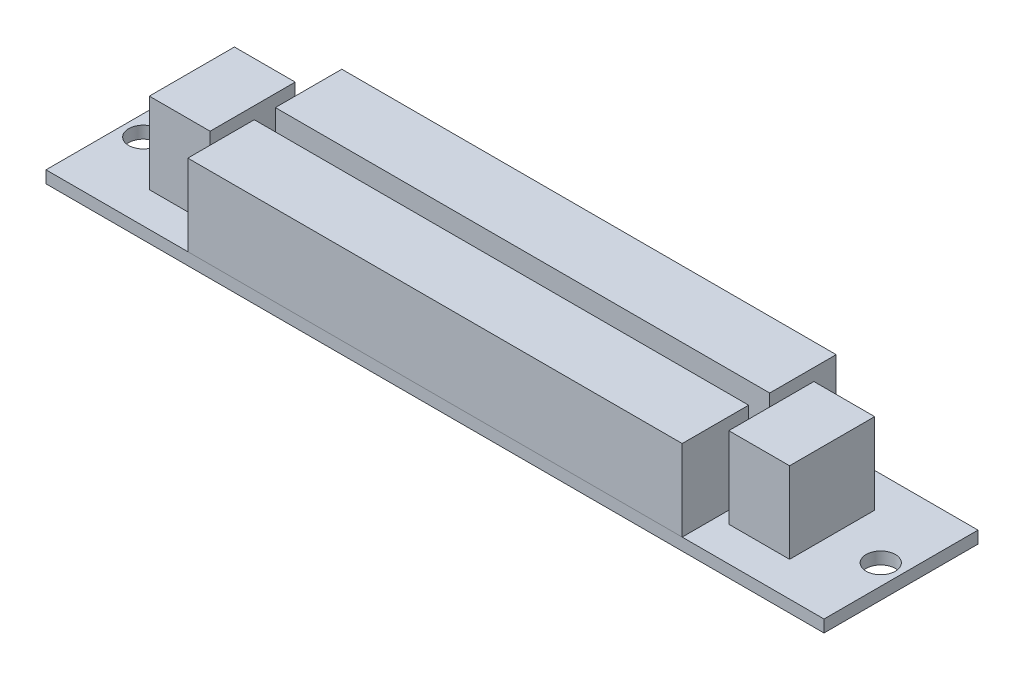
SolidWorks part; units mm, degrees
ref_plane "Front Plane" through (0, 0, 0) normal (0, 0, 1) x (1, 0, 0)
ref_plane "Top Plane" through (0, 0, 0) normal (0, 1, 0) x (1, 0, 0)
ref_plane "Right Plane" through (0, 0, 0) normal (1, 0, 0) x (0, 0, -1)
sketch "Sketch1" plane through (0, 0, 0) normal (0, 1, 0) x (1, 0, 0)
  line L1 (0, 0) -> (96, 0)
  line L2 (0, 0) -> (0, 19)
  line L3 (0, 19) -> (96, 19)
  line L4 (96, 0) -> (96, 19)
  dimension "D1" = 96
  dimension "D2" = 19
extrude "Boss-Extrude1" add sketch "Sketch1" along normal blind 1.5
sketch "Sketch2" plane through (0, 1.5, 0) normal (0, 1, 0) x (1, 0, 0)
  line L0 (0, 9.5) -> (96, 9.5) construction
  line L1 (0, 19) -> (0, 0) construction
  line L2 (96, 0) -> (96, 19) construction
  line L3 (0, 0) -> (96, 0) construction
  line L4 (8.5, 19) -> (87.5, 19)
  line L5 (8.5, 19) -> (8.5, 0)
  line L6 (8.5, 0) -> (87.5, 0)
  line L7 (87.5, 19) -> (87.5, 0)
  line L8 (8.5, 19) -> (87.5, 0) construction
  line L9 (8.5, 0) -> (87.5, 19) construction
  point P6 (48, 9.5)
  dimension "D1" = 79
extrude "Boss-Extrude2" add sketch "Sketch2" along normal blind 10 separate body
sketch "Sketch3" plane through (0, 1.5, 0) normal (0, 1, 0) x (1, 0, 0)
  line L0 (48, 19) -> (48, 0) construction
  line L1 (87.5, 19) -> (8.5, 19) construction
  line L2 (8.5, 0) -> (87.5, 0) construction
  line L3 (2.5, 9.5) -> (93.5, 9.5) construction
  point P7 (93.5, 9.5)
  point P8 (2.5, 9.5)
  point P9 (48, 9.5)
  dimension "D1" = 91
hole_wizard "M3 Clearance Hole1" positions "Sketch3" profile "Sketch4" hole size "M3" standard "ANSI Metric"
sketch "Sketch4" plane through (2.5, 1.5, -9.5) normal (1, 0, 0) x (0, 0, 1)
  line L0 (0, 0) -> (0, 1.5)
  line L1 (0, 1.5) -> (1.8, 1.5)
  line L2 (1.8, 1.5) -> (1.8, 0)
  line L5 (1.8, 0) -> (0, 0)
  line L11 (0, -6.35) -> (0, 107.95) construction
  dimension "Thru Hole Dia." = 3.6
  dimension "Thru Hole Depth" = 1.5
sketch "Sketch5" plane through (0, 11.5, 0) normal (0, 1, 0) x (1, 0, 0)
  line L0 (8.5, 9.5) -> (87.5, 9.5) construction
  line L1 (8.5, 19) -> (8.5, 0) construction
  line L2 (87.5, 0) -> (87.5, 19) construction
  line L3 (8.5, 9.5) -> (16, 9.5) construction
  line L4 (8.5, 4.25) -> (16, 4.25) construction
  line L5 (8.5, 4.25) -> (8.5, 14.75) construction
  line L6 (8.5, 14.75) -> (16, 14.75) construction
  line L7 (16, 4.25) -> (16, 14.75) construction
  line L8 (8.5, 0) -> (87.5, 0) construction
  line L9 (16, 14.75) -> (8.5, 14.75)
  line L10 (16, 14.75) -> (16, 19)
  line L11 (16, 19) -> (8.5, 19)
  line L12 (8.5, 14.75) -> (8.5, 19)
  line L13 (16, 4.25) -> (8.5, 4.25)
  line L14 (16, 4.25) -> (16, 0)
  line L15 (16, 0) -> (8.5, 0)
  line L16 (8.5, 4.25) -> (8.5, 0)
  line L17 (78.5, 8.2) -> (17.5, 8.2)
  line L18 (78.5, 8.2) -> (78.5, 10.8)
  line L19 (78.5, 10.8) -> (17.5, 10.8)
  line L20 (17.5, 8.2) -> (17.5, 10.8)
  line L21 (78.5, 8.2) -> (17.5, 10.8) construction
  line L22 (78.5, 10.8) -> (17.5, 8.2) construction
  line L23 (16, 19) -> (17.5, 19)
  line L24 (16, 19) -> (16, 0)
  line L25 (16, 0) -> (17.5, 0)
  line L26 (17.5, 19) -> (17.5, 0)
  line L27 (48, 19) -> (48, 0) construction
  line L28 (87.5, 19) -> (8.5, 19) construction
  line L29 (17.5, 10.8) -> (78.5, 8.2) construction
  line L30 (17.5, 8.2) -> (78.5, 10.8) construction
  line L31 (80, 4.25) -> (80, 14.75) construction
  line L32 (87.5, 14.75) -> (80, 14.75) construction
  line L33 (87.5, 4.25) -> (87.5, 14.75) construction
  line L34 (87.5, 4.25) -> (80, 4.25) construction
  line L35 (87.5, 9.5) -> (80, 9.5) construction
  line L36 (78.5, 19) -> (78.5, 0)
  line L37 (80, 0) -> (78.5, 0)
  line L38 (80, 19) -> (80, 0)
  line L39 (80, 19) -> (78.5, 19)
  line L40 (78.5, 8.2) -> (78.5, 10.8)
  line L41 (87.5, 4.25) -> (87.5, 0)
  line L42 (80, 0) -> (87.5, 0)
  line L43 (80, 4.25) -> (80, 0)
  line L44 (80, 4.25) -> (87.5, 4.25)
  line L45 (87.5, 14.75) -> (87.5, 19)
  line L46 (80, 19) -> (87.5, 19)
  line L47 (80, 14.75) -> (80, 19)
  line L48 (80, 14.75) -> (87.5, 14.75)
  point P16 (48, 9.5)
  line M14 (87.5, 0) -> (87.5, 19)
  line M15 (87.5, 19) -> (8.5, 19)
  line M16 (8.5, 19) -> (8.5, 0)
  line M17 (8.5, 0) -> (87.5, 0)
  dimension "D1" = 10.5
  dimension "D2" = 7.5
  dimension "D3" = 2.6
  dimension "D4" = 1.5
extrude "Cut-Extrude2" cut sketch "Sketch5" against normal blind 10 contours L9 L10 M15 M16 | L14 L13 M16 M17 | L26 L10 L24 L14 L20 M15 M17 | L20 L17 L18 L19 | L38 L36 L18 M15 M17 | L38 L48 M14 M15 | L44 L38 M17 M14
